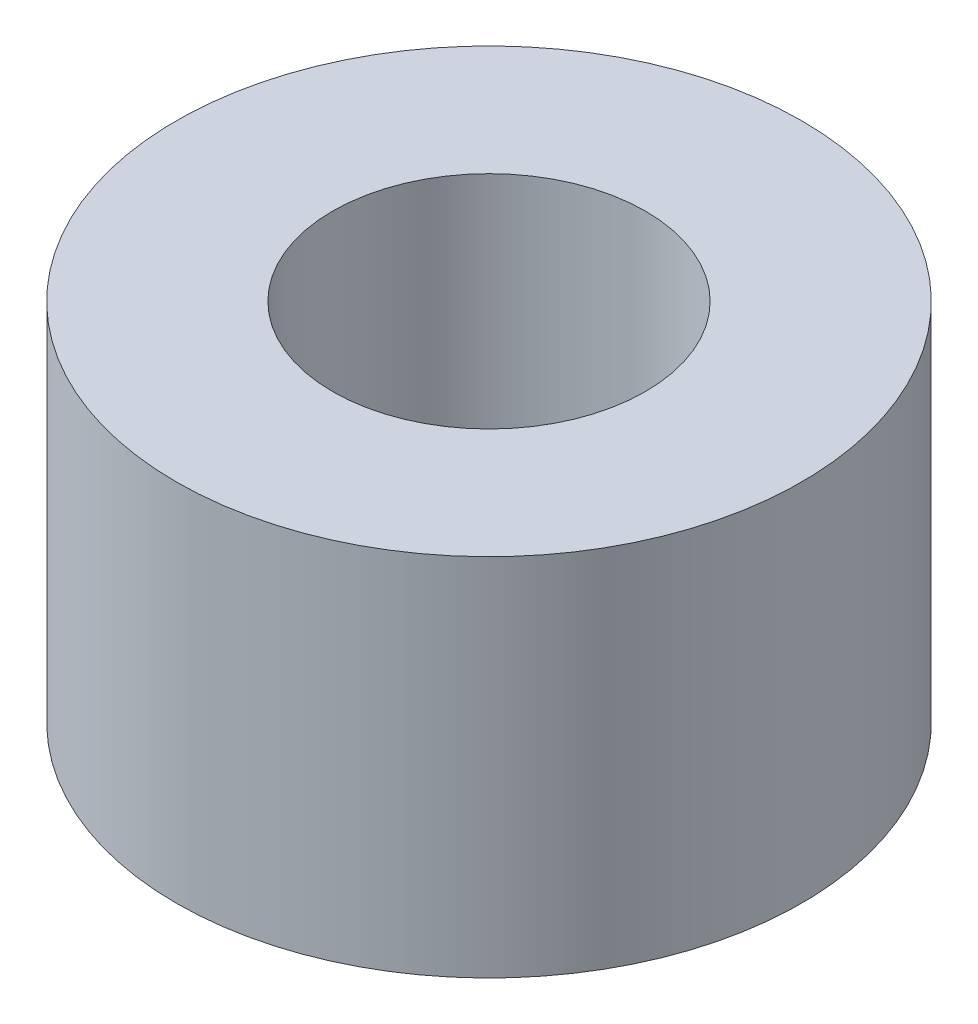
SolidWorks part; units mm, degrees
material "AISI 304"
ref_plane "前视基准面" through (0, 0, 0) normal (0, 0, 1) x (1, 0, 0)
ref_plane "上视基准面" through (0, 0, 0) normal (0, 1, 0) x (1, 0, 0)
ref_plane "右视基准面" through (0, 0, 0) normal (1, 0, 0) x (0, 0, -1)
sketch "草图1" plane through (0, 0, 0) normal (0, 1, 0) x (1, 0, 0)
  circle A0 centre (0, 0) radius 3
  circle A1 centre (0, 0) radius 1.5
  dimension "D1" = 6
  dimension "D2" = 3
extrude "凸台-拉伸1" add sketch "草图1" along normal blind 3.5
